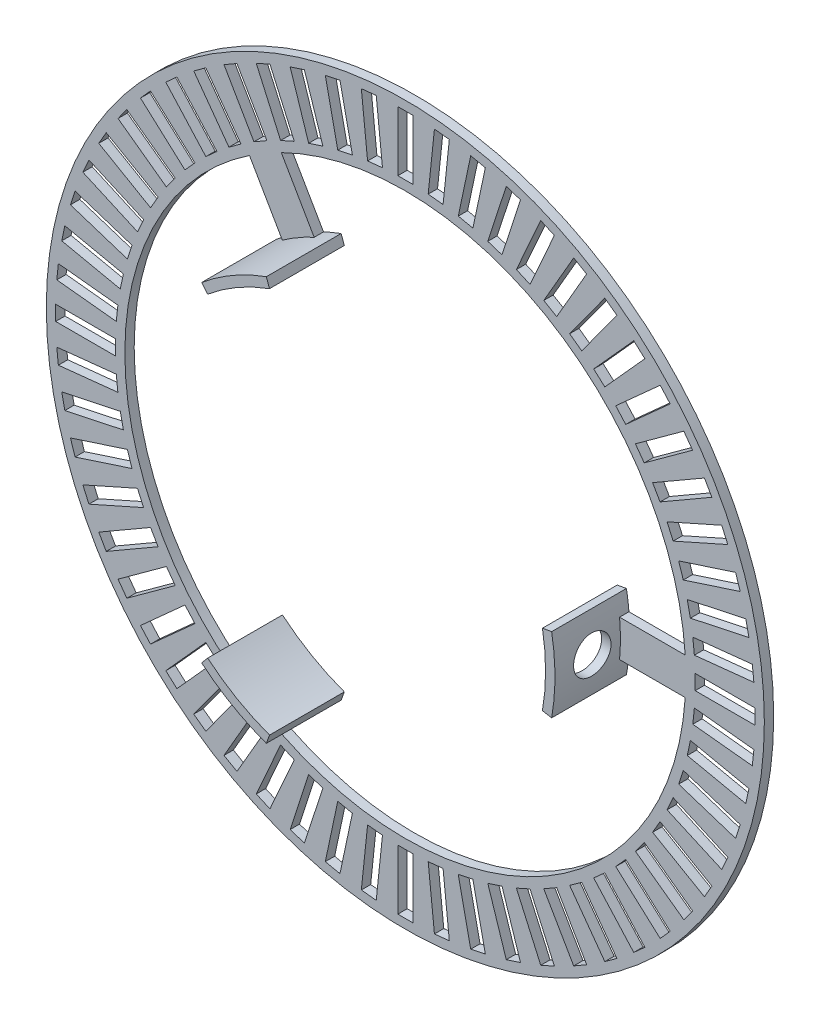
SolidWorks part; units mm, degrees
material "1023 Carbon Steel Sheet (SS)"
ref_plane "Front Plane" through (0, 0, 0) normal (0, 0, 1) x (1, 0, 0)
ref_plane "Top Plane" through (0, 0, 0) normal (0, 1, 0) x (1, 0, 0)
ref_plane "Right Plane" through (0, 0, 0) normal (1, 0, 0) x (0, 0, -1)
sketch "Sketch1" plane through (0, 0, 0) normal (0, 0, 1) x (1, 0, 0)
  circle A0 centre (0, 0) radius 47.625
  circle A1 centre (0, 0) radius 60.96
  dimension "D1" = 121.92
  dimension "D2" = 13.335
extrude "Boss-Extrude1" add sketch "Sketch1" along normal blind 1.5875
sketch "Sketch4" plane through (0, 0, 1.5875) normal (0, 0, 1) x (1, 0, 0)
  line L1 (-1.27, 59.3725) -> (1.27, 59.3725)
  line L2 (-1.27, 59.3725) -> (-1.27, 49.2125)
  line L3 (-1.27, 49.2125) -> (1.27, 49.2125)
  line L4 (1.27, 59.3725) -> (1.27, 49.2125)
  line L5 (-1.27, 59.3725) -> (1.27, 49.2125) construction
  line L6 (-1.27, 49.2125) -> (1.27, 59.3725) construction
  point P0 (0, 54.2925)
  dimension "D1" = 2.54
  dimension "D2" = 10.16
  dimension "D3" = 54.2925
extrude "Cut-Extrude3" cut sketch "Sketch4" against normal blind 5.08 contours L1 L4 L3 L2
pattern_circular "CirPattern2" count 60 over 360 about axis through (0, 0, 0) along (0, 0, 1) of "Cut-Extrude3"
sketch "Sketch7" plane through (0, 0, 0) normal (0, 0, -1) x (-1, 0, 0)
  line L0 (-1.905, 0) -> (49998.095, 0) construction
  circle A2 centre (60.325, 0) radius 6.985
  point P6 (60.325, 0)
  dimension "D1" = 60.325
  dimension "D2" = 13.97
extrude "Cut-Extrude5" [suppressed] cut sketch "Sketch7" against normal blind 2.54
pattern_circular "CirPattern4" [suppressed] count 6 over 360
sketch "Sketch10" plane through (0, 0, 0) normal (0, 0, 1) x (1, 0, 0)
  line L0 (0, 0) -> (23.7079, 0) construction
  line L1 (34.3944, 6.0647) -> (35.9578, 6.3403)
  line L2 (34.3944, -6.0647) -> (35.9578, -6.3403)
  line L3 (-11.9451, -32.8188) -> (-12.488, -34.3105)
  line L4 (-22.4494, -26.7541) -> (-23.4698, -27.9702)
  line L5 (-22.4494, 26.7541) -> (-23.4698, 27.9702)
  line L6 (-11.9451, 32.8188) -> (-12.488, 34.3105)
  arc A0 (34.3944, -6.0647) -> (34.3944, 6.0647) centre (0, 0) ccw
  arc A1 (35.9578, -6.3403) -> (35.9578, 6.3403) centre (0, 0) ccw
  arc A2 (-23.4698, -27.9702) -> (-12.488, -34.3105) centre (0, 0) ccw
  arc A3 (-22.4494, -26.7541) -> (-11.9451, -32.8188) centre (0, 0) ccw
  arc A4 (-12.488, 34.3105) -> (-23.4698, 27.9702) centre (0, 0) ccw
  arc A5 (-11.9451, 32.8188) -> (-22.4494, 26.7541) centre (0, 0) ccw
  point P19 (0, 0)
  dimension "D1" = 69.85
  dimension "D2" = 1.5875
  dimension "D3" = 20
  dimension "D4" = 10
  dimension "D5" = 3
extrude "Boss-Extrude2" add sketch "Sketch10" along normal blind 12.7 separate body contours A0 L1 A1 L2 | A5 L5 A4 L6 | A3 L3 A2 L4
sketch "Sketch12" plane through (0, 0, 0) normal (0, 0, 1) x (1, 0, 0)
  line L0 (0, 0) -> (9.4893, 0) construction
  line L1 (-20.6633, -29.546) -> (-26.7987, -40.1728)
  line L2 (35.9192, -3.122) -> (48.19, -3.122)
  line L3 (35.9192, -3.122) -> (35.9192, 3.122)
  line L4 (35.9192, 3.122) -> (48.19, 3.122)
  line L5 (48.19, -3.122) -> (48.19, 3.122)
  line L6 (35.9192, -3.122) -> (48.19, 3.122) construction
  line L7 (35.9192, 3.122) -> (48.19, -3.122) construction
  line L8 (-20.6633, -29.546) -> (-15.2559, -32.6679)
  line L9 (-15.2559, -32.6679) -> (-21.3913, -43.2947)
  line L10 (-26.7987, -40.1728) -> (-21.3913, -43.2947)
  line L11 (-15.2559, 32.6679) -> (-21.3913, 43.2947)
  line L12 (-15.2559, 32.6679) -> (-20.6633, 29.546)
  line L13 (-20.6633, 29.546) -> (-26.7987, 40.1728)
  line L14 (-21.3913, 43.2947) -> (-26.7987, 40.1728)
  point P1 (42.0546, 0)
  point P20 (0, 0)
  dimension "D1" = 42.0546
  dimension "D2" = 12.2708
  dimension "D3" = 6.2439
  dimension "D4" = 3
extrude "Boss-Extrude4" add sketch "Sketch12" along normal blind 1.5875
sketch "Sketch13" plane through (0, 0, 0) normal (1, 0, 0) x (0, 0, -1)
  line L3 (-6.35, 6.3403) -> (-6.35, -6.3403) construction
  line L4 (-12.7, 6.3403) -> (0, 6.3403) construction
  line L5 (-12.7, -6.3403) -> (0, -6.3403) construction
  circle A0 centre (-6.35, 0) radius 3.175
  dimension "D1" = 6.35
extrude "Cut-Extrude6" cut sketch "Sketch13" along normal through all
equation "\"1inch\"=0.1"
